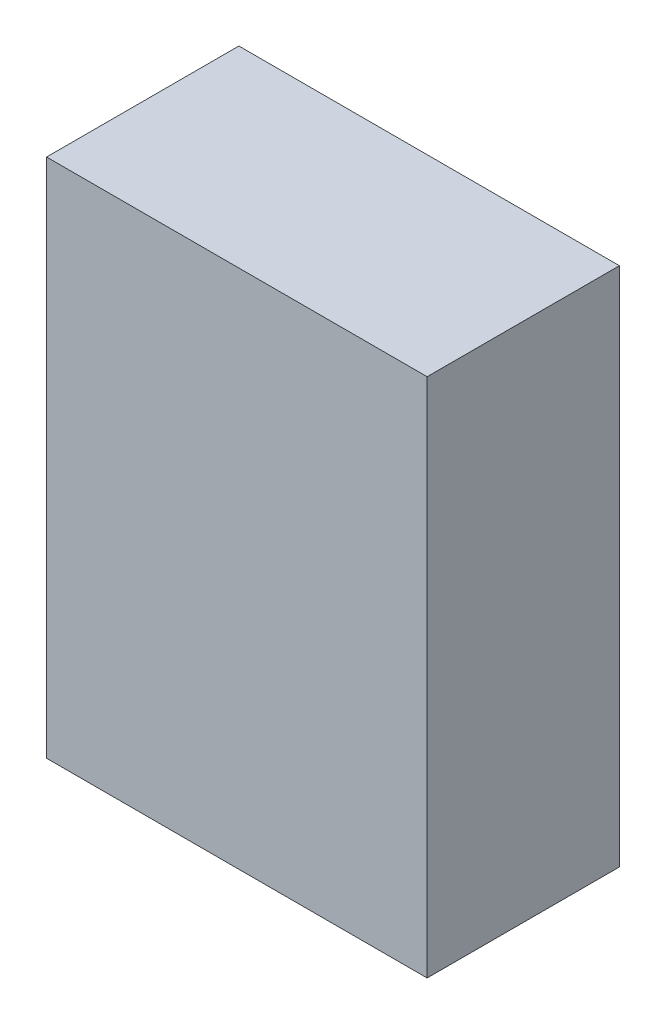
SolidWorks part; units mm, degrees
ref_plane "Plan de face" through (0, 0, 0) normal (0, 0, 1) x (1, 0, 0)
ref_plane "Plan de dessus" through (0, 0, 0) normal (0, 1, 0) x (1, 0, 0)
ref_plane "Plan de droite" through (0, 0, 0) normal (1, 0, 0) x (0, 0, -1)
sketch "Esquisse1" plane through (0, 0, 0) normal (0, 0, 1) x (1, 0, 0)
  line L1 (0, 0) -> (47.5, 0)
  line L2 (0, 0) -> (0, 65)
  line L3 (0, 65) -> (47.5, 65)
  line L4 (47.5, 0) -> (47.5, 65)
  dimension "D1" = 47.5
  dimension "D2" = 65
extrude "Boss.-Extru.1" add sketch "Esquisse1" along normal blind 24
